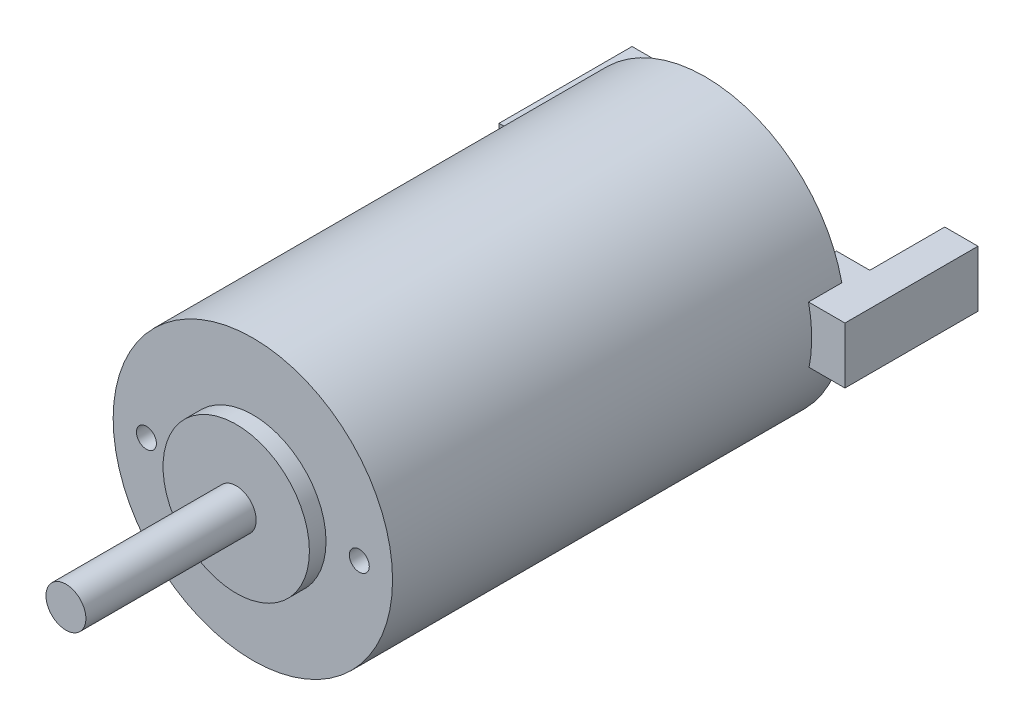
SolidWorks part; units mm, degrees
ref_plane "Alzado" through (0, 0, 0) normal (0, 0, 1) x (1, 0, 0)
ref_plane "Planta" through (0, 0, 0) normal (0, 1, 0) x (1, 0, 0)
ref_plane "Vista lateral" through (0, 0, 0) normal (1, 0, 0) x (0, 0, -1)
sketch "Croquis1" plane through (0, 0, 0) normal (0, 0, 1) x (1, 0, 0)
  circle A0 centre (0, 0) radius 21
  dimension "D1" = 42
extrude "Saliente-Extruir1" add sketch "Croquis1" along normal blind 68
sketch "Croquis2" plane through (0, 0, 68) normal (0, 0, 1) x (1, 0, 0)
  circle A0 centre (0, 0) radius 11
  dimension "D1" = 22
extrude "Saliente-Extruir2" add sketch "Croquis2" along normal blind 2.5
sketch "Croquis3" plane through (0, 0, 70.5) normal (0, 0, 1) x (1, 0, 0)
  circle A0 centre (0, 0) radius 3
  dimension "D1" = 6
extrude "Saliente-Extruir3" add sketch "Croquis3" along normal blind 25.6
ref_plane "Plano1" through (21, 0, 0) normal (1, 0, 0) x (0, 0, -1)
sketch "Croquis4" plane through (21, 0, 0) normal (1, 0, 0) x (0, 0, -1)
  line L2 (15, 4.4374) -> (15, -4.0301)
  line L3 (15, -4.0301) -> (-5, -4.0301)
  line L4 (-5, -4.0301) -> (-5, 4.4374)
  line L6 (-5, 4.4374) -> (15, 4.4374)
  dimension "D1" = 5
  dimension "D2" = 20
extrude "Saliente-Extruir4" add sketch "Croquis4" along normal mid plane 10
ref_plane "Plano2" through (-21, 0, 0) normal (1, 0, 0) x (0, 0, -1)
sketch "Croquis6" plane through (-21, 0, 0) normal (1, 0, 0) x (0, 0, -1)
  line L1 (-5, 4.4374) -> (15, 4.4374)
  line L2 (-5, 4.4374) -> (-5, -4.0301)
  line L3 (-5, -4.0301) -> (15, -4.0301)
  line L4 (15, 4.4374) -> (15, -4.0301)
extrude "Saliente-Extruir5" add sketch "Croquis6" along normal mid plane 10
sketch "Croquis7" plane through (0, 4.4374, 0) normal (0, 1, 0) x (1, 0, 0)
  line L0 (16, 3.735) -> (21, 3.735)
  line L1 (16, 15) -> (16, 0) construction
  line L2 (21, -23.1) -> (21, 23.1) construction
  line L3 (21, 3.735) -> (21, 15)
  line L4 (26, 15) -> (16, 15) construction
  line L5 (21, 15) -> (-21, 15)
  line L6 (-16, 15) -> (-26, 15) construction
  line L7 (-21, 15) -> (-21, 3.735)
  line L8 (-21, -23.1) -> (-21, 23.1) construction
  line L9 (-21, 3.735) -> (16, 3.735)
extrude "Cortar-Extruir1" cut sketch "Croquis7" against normal through all
sketch "Croquis8" plane through (0, 0, 68) normal (0, 0, 1) x (1, 0, 0)
  circle A2 centre (-16, 0) radius 1.5
  circle A3 centre (16, 0) radius 1.5
  dimension "D2" = 3
  dimension "D3" = 3
extrude "Cortar-Extruir2" cut sketch "Croquis8" against normal blind 10
